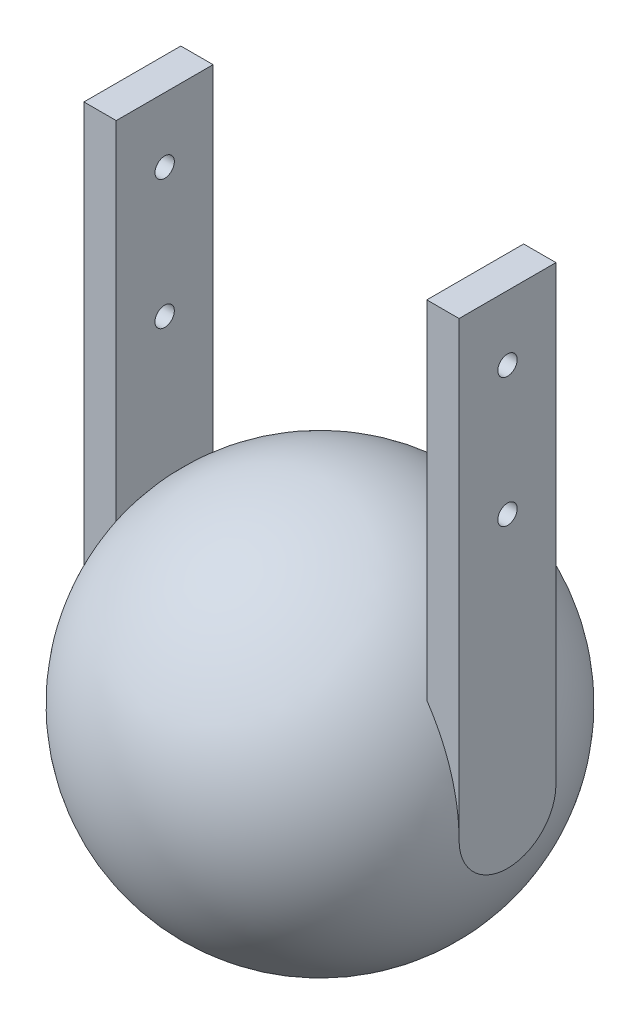
SolidWorks part; units mm, degrees
ref_plane "Front Plane" through (0, 0, 0) normal (0, 0, 1) x (1, 0, 0)
ref_plane "Top Plane" through (0, 0, 0) normal (0, 1, 0) x (1, 0, 0)
ref_plane "Right Plane" through (0, 0, 0) normal (1, 0, 0) x (0, 0, -1)
sketch "Sketch2" plane through (0, 0, 0) normal (0, 1, 0) x (1, 0, 0)
  line L0 (29.0474, 7.5) -> (29.0474, -7.5)
  line L1 (-29.0474, -7.5) -> (-29.0474, 7.5)
  line L2 (-29.0474, 0) -> (29.0474, 0)
  circle A0 centre (0, 0) radius 30 construction
  arc A1 (-29.0474, 7.5) -> (29.0474, 7.5) centre (0, 0) cw
  arc A2 (-29.0474, -7.5) -> (29.0474, -7.5) centre (0, 0) ccw construction
  dimension "D1" = 60
  dimension "D2" = 15
revolve "Revolve1" add sketch "Sketch2" angle 360 about L2
sketch "Sketch3" plane through (-29.0474, 0, 0) normal (-1, 0, 0) x (0, 0, 1)
  line L0 (-7.5, 0) -> (7.5, 0) construction
  line L1 (-7.5, 0) -> (-7.5, 70)
  line L2 (-7.5, 70) -> (7.5, 70)
  line L3 (7.5, 70) -> (7.5, 0)
  circle A0 centre (0, 0) radius 7.5 construction
  arc A1 (-7.5, 0) -> (7.5, 0) centre (0, 0) ccw
  dimension "D1" = 70
extrude "Boss-Extrude1" add sketch "Sketch3" against normal blind 5 contours L3 A1 L1 L2
ref_plane "Plane1" through (0, 0, 0) normal (1, 0, 0) x (0, 0, -1)
mirror "Mirror1" about plane through (0, 0, 0) normal (1, 0, 0) of "Boss-Extrude1"
sketch "Sketch4" plane through (-29.0474, 0, 0) normal (-1, 0, 0) x (0, 0, 1)
  line L1 (-7.5, 70) -> (7.5, 70) construction
  point P0 (0, 60)
  point P1 (0, 40)
  point P3 (0, 70)
  dimension "D1" = 10
  dimension "D2" = 20
hole_wizard "Ø3.0mm Dowel Hole1" positions "Sketch4" profile "Sketch5" hole size "Ø3.0" standard "ANSI Metric"
sketch "Sketch5" plane through (-29.0474, 60, 0) normal (0, 1, 0) x (0, 0, 1)
  line L0 (0, 0) -> (0, 58.0948)
  line L1 (0, 58.0948) -> (1.5, 58.0948)
  line L2 (1.5, 58.0948) -> (1.5, 0)
  line L5 (1.5, 0) -> (0, 0)
  line L11 (0, -6.35) -> (0, 107.95) construction
  dimension "Thru Hole Dia." = 3
  dimension "Thru Hole Depth" = 58.0948
equation "\"jointdiameter\"= 60"
equation "\"D1@Sketch2\"=\"jointdiameter\""
equation "\"flatlength\"= 15"
equation "\"D2@Sketch2\"=\"flatlength\""
equation "\"mountlength\"= 40 + \"jointdiameter\" / 2"
equation "\"D1@Sketch3\"=\"mountlength\""
equation "\"mountthick\"= 5"
equation "\"D1@Boss-Extrude1\"=\"mountthick\""
